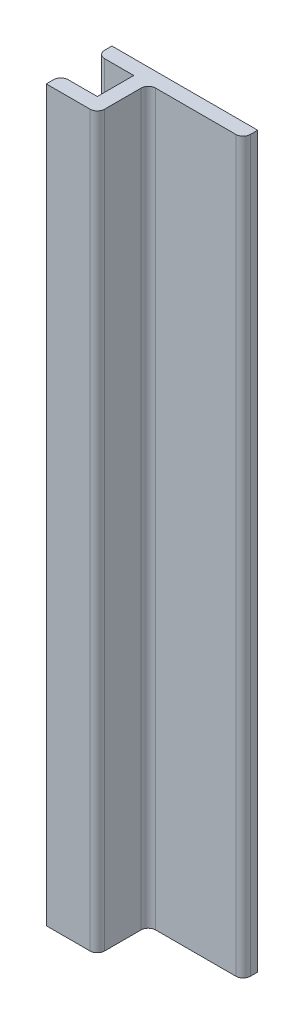
SolidWorks part; units mm, degrees
ref_plane "Front Plane" through (0, 0, 0) normal (0, 0, 1) x (1, 0, 0)
ref_plane "Top Plane" through (0, 0, 0) normal (0, 1, 0) x (1, 0, 0)
ref_plane "Right Plane" through (0, 0, 0) normal (1, 0, 0) x (0, 0, -1)
sketch "Sketch1" plane through (0, 0, 0) normal (0, 1, 0) x (1, 0, 0)
  line L0 (-24.9296, 0) -> (27.7465, 0) construction
  line L1 (0, -18.0986) -> (0, -7) construction
  line L2 (0, 0) -> (20, 0)
  line L3 (20, 0) -> (20, -2)
  line L4 (20, -2) -> (7, -2)
  line L5 (7, -2) -> (7, -9)
  line L6 (7, -9) -> (0, -9)
  line L7 (0, -9) -> (0, -7)
  line L8 (0, -7) -> (5, -7)
  line L9 (5, -7) -> (5, -2)
  line L10 (5, -2) -> (0, -2)
  line L11 (0, -2) -> (0, 18.662) construction
  line L12 (0, -2) -> (0, 0)
  dimension "D1" = 20
  dimension "D2" = 2
  dimension "D3" = 2
  dimension "D4" = 5
  dimension "D5" = 2
  dimension "D6" = 2
  dimension "D7" = 5
extrude "Boss-Extrude1" add sketch "Sketch1" along normal blind 100
fillet "Fillet1" radius 1 5 edges at (0, 50, 7) (0, 50, 2) (7, 50, 9) (7, 50, 2) (20, 50, 2)
